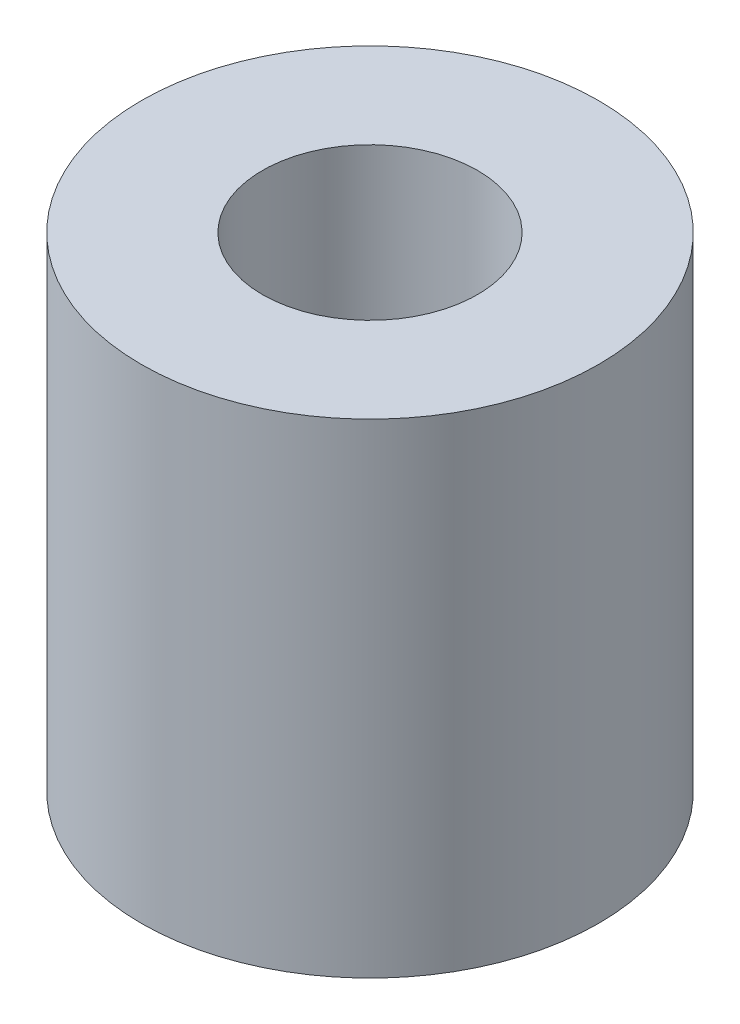
SolidWorks part; units mm, degrees
ref_plane "Front Plane" through (0, 0, 0) normal (0, 0, 1) x (1, 0, 0)
ref_plane "Top Plane" through (0, 0, 0) normal (0, 1, 0) x (1, 0, 0)
ref_plane "Right Plane" through (0, 0, 0) normal (1, 0, 0) x (0, 0, -1)
sketch "Sketch1" plane through (0, 0, 0) normal (0, 1, 0) x (1, 0, 0)
  circle A0 centre (0, 0) radius 5.3975
  circle A1 centre (0, 0) radius 2.54
  dimension "D1" = 10.795
  dimension "D2" = 5.08
extrude "Boss-Extrude1" add sketch "Sketch1" along normal blind 11.43
